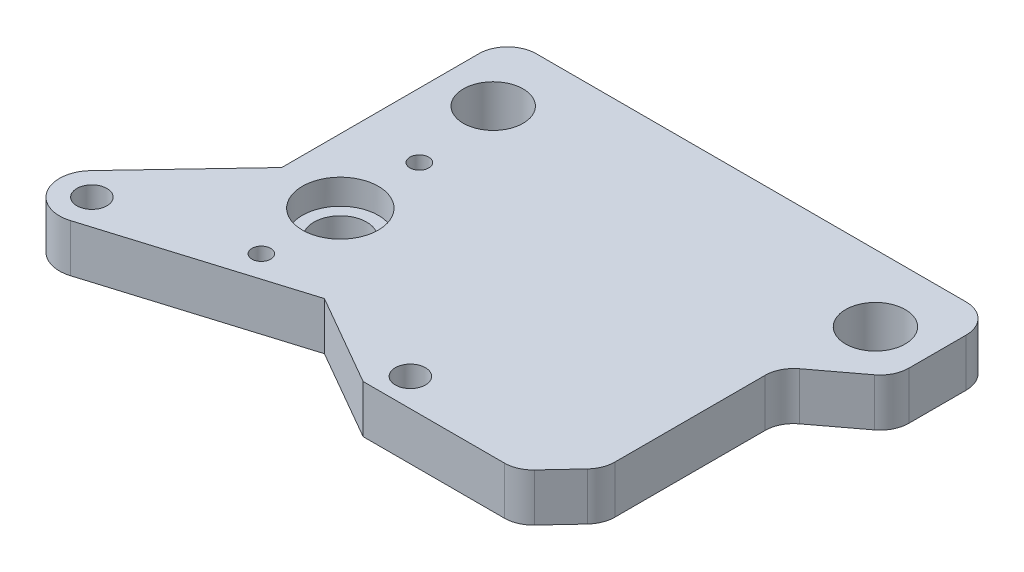
SolidWorks part; units mm, degrees
other "Markup1"
sketch "Sketch6" plane through (-23.3268, 0, -30.7975) normal (-0.0348, 0.9994, -0.0028) x (-0.9993, -0.0348, 0.0153)
sketch "Sketch7" plane through (-23.3268, 0, -30.7975) normal (-0.0348, 0.9994, -0.0028) x (-0.9993, -0.0348, 0.0153)
sketch "Sketch8" plane through (-23.3268, 0, -30.7975) normal (-0.0348, 0.9994, -0.0028) x (-0.9993, -0.0348, 0.0153)
sketch "Sketch10" plane through (-23.3268, 0, -30.7975) normal (-0.0348, 0.9994, -0.0028) x (-0.9993, -0.0348, 0.0153)
sketch "Sketch13" plane through (-23.3268, 0, -30.7975) normal (-0.0348, 0.9994, -0.0028) x (-0.9993, -0.0348, 0.0153)
sketch "Sketch15" plane through (-23.3268, 0, -30.7975) normal (-0.0348, 0.9994, -0.0028) x (-0.9993, -0.0348, 0.0153)
sketch "Sketch16" [suppressed] plane through (-23.3268, 0, -30.7975) normal (-0.0348, 0.9994, -0.0028) x (-0.9993, -0.0348, 0.0153)
sketch "Sketch17" plane through (-23.3268, 0, -30.7975) normal (-0.0348, 0.9994, -0.0028) x (-0.9993, -0.0348, 0.0153)
sketch "Sketch18" plane through (-23.3268, 0, -30.7975) normal (-0.0348, 0.9994, -0.0028) x (-0.9993, -0.0348, 0.0153)
sketch "Sketch19" [suppressed] plane through (-23.3268, 0, -30.7975) normal (-0.0348, 0.9994, -0.0028) x (-0.9993, -0.0348, 0.0153)
sketch "Sketch21" plane through (-23.3268, 0, -30.7975) normal (-0.0348, 0.9994, -0.0028) x (-0.9993, -0.0348, 0.0153)
sketch "Sketch23" plane through (-23.3268, 0, -30.7975) normal (-0.0348, 0.9994, -0.0028) x (-0.9993, -0.0348, 0.0153)
sketch "Sketch24" plane through (-23.3268, 0, -30.7975) normal (-0.0348, 0.9994, -0.0028) x (-0.9993, -0.0348, 0.0153)
sketch "Sketch25" plane through (-23.3268, 0, -30.7975) normal (-0.0348, 0.9994, -0.0028) x (-0.9993, -0.0348, 0.0153)
sketch "Sketch26" [suppressed] plane through (-23.3268, 0, -30.7975) normal (-0.0348, 0.9994, -0.0028) x (-0.9993, -0.0348, 0.0153)
sketch "Sketch27" plane through (-23.3268, 0, -30.7975) normal (-0.0348, 0.9994, -0.0028) x (-0.9993, -0.0348, 0.0153)
sketch "Sketch28" plane through (-23.3268, 0, -30.7975) normal (-0.0348, 0.9994, -0.0028) x (-0.9993, -0.0348, 0.0153)
sketch "Sketch29" plane through (-23.3268, 0, -30.7975) normal (-0.0348, 0.9994, -0.0028) x (-0.9993, -0.0348, 0.0153)
sketch "Sketch30" plane through (-23.3268, 0, -30.7975) normal (-0.0348, 0.9994, -0.0028) x (-0.9993, -0.0348, 0.0153)
sketch "Sketch32" plane through (-23.3268, 0, -30.7975) normal (-0.0348, 0.9994, -0.0028) x (-0.9993, -0.0348, 0.0153)
sketch "Sketch34" [suppressed] plane through (-23.3268, 0, -30.7975) normal (-0.0348, 0.9994, -0.0028) x (-0.9993, -0.0348, 0.0153)
sketch "Sketch35" [suppressed] plane through (-23.3268, 0, -30.7975) normal (-0.0348, 0.9994, -0.0028) x (-0.9993, -0.0348, 0.0153)
sketch "Sketch36" [suppressed] plane through (-23.3268, 0, -30.7975) normal (-0.0348, 0.9994, -0.0028) x (-0.9993, -0.0348, 0.0153)
sketch "Sketch37" plane through (-23.3268, 0, -30.7975) normal (-0.0348, 0.9994, -0.0028) x (-0.9993, -0.0348, 0.0153)
sketch "Sketch38" plane through (-23.3268, 0, -30.7975) normal (-0.0348, 0.9994, -0.0028) x (-0.9993, -0.0348, 0.0153)
sketch "Sketch39" [suppressed] plane through (-23.3268, 0, -30.7975) normal (-0.0348, 0.9994, -0.0028) x (-0.9993, -0.0348, 0.0153)
sketch "Sketch40" plane through (-23.3268, 0, -30.7975) normal (-0.0348, 0.9994, -0.0028) x (-0.9993, -0.0348, 0.0153)
sketch "Sketch41" plane through (-23.3268, 0, -30.7975) normal (-0.0348, 0.9994, -0.0028) x (-0.9993, -0.0348, 0.0153)
material "6061-T6 (SS)"
ref_plane "X-Y Datum" through (0, 0, 0) normal (0, 0, 1) x (1, 0, 0)
ref_plane "X-Z Datum" through (0, 0, 0) normal (0, 1, 0) x (1, 0, 0)
ref_plane "Y-Z Datum" through (0, 0, 0) normal (1, 0, 0) x (0, 0, -1)
other "Graphic1"
other "Graphic (Closed) -1"
other "Graphic (Closed) -2"
sketch "Sketch2" plane through (0, 0, 0) normal (0, 1, 0) x (1, 0, 0)
  line L0 (48.6426, -18.7325) -> (-23.0162, -18.7325)
  line L1 (24.0125, -14.7036) -> (25.7865, -13.7801) construction
  line L2 (0, 0) -> (105.5557, -202.7707) construction
  line L3 (11.142, -21.4036) -> (-3.5026, -29.027) construction
  line L4 (0, 0) -> (0, -121.3797) construction
  line L5 (-3.5026, -29.027) -> (90.9112, -210.3941) construction
  line L6 (90.9112, -210.3941) -> (105.5557, -202.7707) construction
  line L7 (11.142, -21.4036) -> (24.0125, -14.7036) construction
  line L11 (-12.7, 30.7975) -> (57.15, 30.7975)
  line L12 (57.15, 13.0175) -> (57.15, 30.7975)
  line L13 (57.15, 13.0175) -> (-12.7, 13.0175) construction
  line L15 (44.7685, -18.0975) -> (44.7685, -11.3157) construction
  line L16 (44.7685, -18.0975) -> (34.8625, -18.0975) construction
  line L18 (44.7685, 9.8425) -> (34.8625, 9.8425) construction
  line L20 (44.7685, -11.3157) -> (49.8485, -11.3157) construction
  line L21 (49.8485, -11.3157) -> (49.8485, 3.0607) construction
  line L22 (49.8485, 3.0607) -> (44.7685, 3.0607) construction
  line L23 (44.7685, 3.0607) -> (44.7685, 9.8425) construction
  line L24 (34.8625, -18.0975) -> (34.8625, 9.8425) construction
  line L25 (48.6426, -18.7325) -> (57.15, 13.0175)
  line L26 (-12.7, 30.7975) -> (-12.7, 13.0175)
  line L28 (-12.5603, 0) -> (-16.51, -40.5272) construction
  line L30 (-23.0162, -18.7325) -> (-12.7, 13.0175)
  circle A0 centre (0, 0) radius 3.175
  circle A1 centre (24.0125, -14.7036) radius 2
  circle A2 centre (-1.5875, 21.9075) radius 3.9688
  circle A3 centre (49.2125, 21.9075) radius 3.9687
  circle A4 centre (39.8485, -4.1275) radius 5.1
  circle A5 centre (24.0125, -14.7036) radius 3.175 construction
  circle A6 centre (39.8485, -14.6275) radius 1.6
  circle A7 centre (39.8485, 6.3725) radius 1.6
  circle A8 centre (-17.2047, -14.9225) radius 3.175 construction
  circle A9 centre (-17.2047, -14.9225) radius 2
  point P9 (11.142, -21.4036)
  point P30 (49.8485, -4.1275)
  point P31 (34.8625, -4.1275)
  dimension "D1" = 6.35
  dimension "D8" = 4
  dimension "D10" = 7.9375
  dimension "D11" = 7.9375
  dimension "D16" = 27.94
  dimension "D23" = 10.2
  dimension "D20" = 6.35
  dimension "D30" = 3.2
  dimension "D32" = 3.2
  dimension "D34" = 6.35
  dimension "D35" = 4
  dimension "D3" = 13.0175
  dimension "D4" = 16.51
  dimension "D5" = 228.6
  dimension "D6" = 24.13
  dimension "D7" = 27.5
  dimension "D9" = 16.51
  dimension "D12" = 8.89
  dimension "D13" = 69.85
  dimension "D14" = 7.9375
  dimension "D15" = 31.75
  dimension "D17" = 17.78
  dimension "D18" = 3.175
  dimension "D19" = 14.986
  dimension "D21" = 5.08
  dimension "D22" = 14.3764
  dimension "D24" = 10
  dimension "D25" = 36.83
  dimension "D26" = 50.8
  dimension "D27" = 165
  dimension "D28" = 12.7
  dimension "D29" = 17.3015
  dimension "D31" = 10.5
  dimension "D33" = 10.5
  dimension "D36" = 162
extrude "Boss-Extrude1" [suppressed] add sketch "Sketch2" against normal blind 6.35
ref_point "Point1" [suppressed]
sketch "Sketch3" [suppressed] plane through (0, 0, 0) normal (0, 1, 0) x (1, 0, 0)
  line L0 (39.9681, 6.3725) -> (39.9681, -4.1275) construction
  line L1 (57.2697, 12.9663) -> (-12.5803, 12.9663) construction
  line L5 (39.9681, -4.1275) -> (39.9681, -14.6275) construction
  line L6 (42.0297, -18.7325) -> (20.4164, -18.7325)
  line L7 (57.2697, 12.9663) -> (57.2697, 30.7975)
  line L8 (57.2697, 30.7975) -> (-12.5803, 30.7975)
  line L9 (-12.5803, 30.7975) -> (-12.5803, 12.9663)
  line L10 (40.938, 24.6176) -> (16.9472, 10.7666)
  line L11 (13.3942, 11.8528) -> (6.9035, 25.1608)
  line L12 (8.045, 26.9875) -> (40.303, 26.9875)
  line L13 (57.2697, 12.9663) -> (48.3797, 12.9663)
  line L14 (48.3797, 12.9663) -> (48.3797, -12.3825)
  line L16 (-23.0162, -18.7325) -> (48.6426, -18.7325) construction
  line L18 (16.6064, -14.8627) -> (10.2787, -14.8627)
  line L21 (-8.965, -15.5427) -> (-15.106, -18.7325)
  line L24 (-21.1701, -13.6017) -> (-12.5803, 12.9663)
  line L29 (17.8764, -16.1925) -> (17.8764, -16.1327)
  circle A0 centre (0.1197, 0) radius 3.175
  circle A1 centre (-1.4678, 21.9075) radius 3.9688
  circle A2 centre (49.3322, 21.9075) radius 3.9687
  circle A3 centre (39.9681, -4.1275) radius 5.1
  circle A4 centre (39.9681, -14.6275) radius 1.6
  circle A5 centre (39.9681, 6.3725) radius 1.6
  circle A6 centre (24.1322, -14.7036) radius 2
  circle A7 centre (-17.085, -14.9225) radius 2
  arc A8 (13.3942, 11.8528) -> (16.9472, 10.7666) centre (15.6772, 12.9663) ccw
  arc A9 (8.045, 26.9875) -> (6.9035, 25.1608) centre (8.045, 25.7175) ccw
  arc A10 (40.938, 24.6176) -> (40.303, 26.9875) centre (40.303, 25.7175) ccw
  arc A11 (10.2787, -14.8627) -> (-8.965, -15.5427) centre (0.1197, 0) cw
  arc A12 (-15.106, -18.7325) -> (-21.1701, -13.6017) centre (-17.085, -14.9225) cw
  arc A13 (42.0297, -18.7325) -> (48.3797, -12.3825) centre (42.0297, -12.3825) ccw
  arc A14 (20.4164, -18.7325) -> (17.8764, -16.1925) centre (20.4164, -16.1925) cw
  arc A15 (16.6064, -14.8627) -> (17.8764, -16.1327) centre (16.6064, -16.1327) cw
  dimension "D1" = 6.35
  dimension "D4" = 7.9375
  dimension "D9" = 10.2
  dimension "D10" = 3.2
  dimension "D11" = 4
  dimension "D21" = 2.54
  dimension "D22" = 1.27
  dimension "D3" = 6.35
  dimension "D28" = 2.54
  dimension "D29" = 1.27
  dimension "D2" = 7.9375
  dimension "D5" = 50.8
  dimension "D6" = 21.9075
  dimension "D7" = 1.5875
  dimension "D8" = 8.89
  dimension "D12" = 10.5
  dimension "D13" = 17.2047
  dimension "D14" = 24.0125
  dimension "D15" = 14.7036
  dimension "D16" = 39.8485
  dimension "D17" = 4.1275
  dimension "D18" = 14.9225
  dimension "D19" = 69.85
  dimension "D20" = 3.81
  dimension "D23" = 30
  dimension "D24" = 64
  dimension "D25" = 32.258
  dimension "D26" = 15.5575
  dimension "D27" = 25.3488
  dimension "D30" = 8.89
sketch "Sketch4" plane through (0, 0, 0) normal (0, 1, 0) x (1, 0, 0)
  line L0 (39.8485, 6.3725) -> (39.8485, -4.1275) construction
  line L1 (56.1975, 13.0175) -> (-8.5725, 13.0175) construction
  line L2 (39.8485, -4.1275) -> (39.8485, -14.6275) construction
  line L3 (40.2577, -18.4375) -> (21.466, -18.4375)
  line L5 (52.3875, 30.7975) -> (-4.7625, 30.7975)
  line L6 (-8.5725, 26.9875) -> (-8.5725, 0.7817)
  line L40 (47.4685, 8.9851) -> (47.4685, -10.9806)
  line L41 (46.4449, -13.579) -> (43.0442, -17.2259)
  line L43 (48.9856, 12.0279) -> (54.6804, 16.3193)
  line L44 (56.1975, 19.3621) -> (56.1975, 26.9875)
  line L48 (-8.5725, 0.7817) -> (-20.9174, -12.2732)
  line L50 (-17.78, -15.24) -> (0, 0) construction
  line L58 (21.466, -18.4375) -> (9.3466, -11.4637)
  line L59 (0, 0) -> (0, 5.6144) construction
  line L60 (9.3466, -11.4637) -> (-16.5178, -19.3694)
  circle A0 centre (0, 0) radius 5.05
  circle A1 centre (-1.5875, 21.9075) radius 3.9688
  circle A2 centre (49.2125, 21.9075) radius 3.9687
  circle A6 centre (24.0125, -14.7036) radius 2
  circle A7 centre (-17.78, -15.24) radius 2
  arc A12 (-15.328, -18.7942) -> (-20.9174, -12.2732) centre (-17.78, -15.24) cw
  arc A19 (-8.5725, 26.9875) -> (-4.7625, 30.7975) centre (-4.7625, 26.9875) cw
  arc A20 (52.3875, 30.7975) -> (56.1975, 26.9875) centre (52.3875, 26.9875) cw
  circle A33 centre (24.0125, -14.7036) radius 3.5 construction
  arc A45 (56.1975, 19.3621) -> (54.6804, 16.3193) centre (52.3875, 19.3621) cw
  arc A46 (47.4685, 8.9851) -> (48.9856, 12.0279) centre (51.2785, 8.9851) cw
  arc A47 (47.4685, -10.9806) -> (46.4449, -13.579) centre (43.6585, -10.9806) cw
  arc A48 (43.0442, -17.2259) -> (40.2577, -18.4375) centre (40.2577, -14.6275) cw
  circle A49 centre (0, -10.5) radius 1.25
  circle A50 centre (0, 10.5) radius 1.25
  point P58 (-8.5725, 30.7975)
  point P77 (56.1975, 17.4625)
  point P84 (41.9143, -18.4375)
  dimension "D1" = 10.1
  dimension "D2" = 7.9375
  dimension "D8" = 4
  dimension "D25" = 3.81
  dimension "D26" = 7
  dimension "D33" = 4.318
  dimension "D38" = 10.5
  dimension "D23" = 3.81
  dimension "D46" = 2.5
  dimension "D45" = 3.81
  dimension "D3" = 50.8
  dimension "D4" = 21.9075
  dimension "D5" = 1.5875
  dimension "D9" = 10.5
  dimension "D10" = 24.0125
  dimension "D11" = 14.7036
  dimension "D12" = 39.8485
  dimension "D13" = 4.1275
  dimension "D14" = 15.24
  dimension "D15" = 17.78
  dimension "D16" = 6.985
  dimension "D17" = 8.89
  dimension "D21" = 17.78
  dimension "D24" = 7.62
  dimension "D36" = 9.525
  dimension "D40" = 127
  dimension "D41" = 10.5
  dimension "D43" = 137
  dimension "D60" = 6.985
extrude "Boss-Extrude2" add sketch "Sketch4" against normal blind 6.35
ref_point "Point2"
ref_point "Point3"
ref_point "Point4"
sketch "Sketch31" plane through (0, -6.35, 0) normal (0, -1, 0) x (1, 0, 0)
  circle A0 centre (0, 0) radius 3.5
  circle A1 centre (0, 0) radius 6.35
  dimension "D1" = 7
  dimension "D2" = 12.7
extrude "Boss-Extrude5" add sketch "Sketch31" against normal blind 3
sketch "Sketch33" [suppressed] plane through (0, 0, 0) normal (0, 1, 0) x (1, 0, 0)
  circle A0 centre (0, 0) radius 6.35
  circle A1 centre (0, 0) radius 3.5
  dimension "D1" = 7
  dimension "D2" = 12.7
extrude "Boss-Extrude6" [suppressed] add sketch "Sketch33" against normal blind 3
